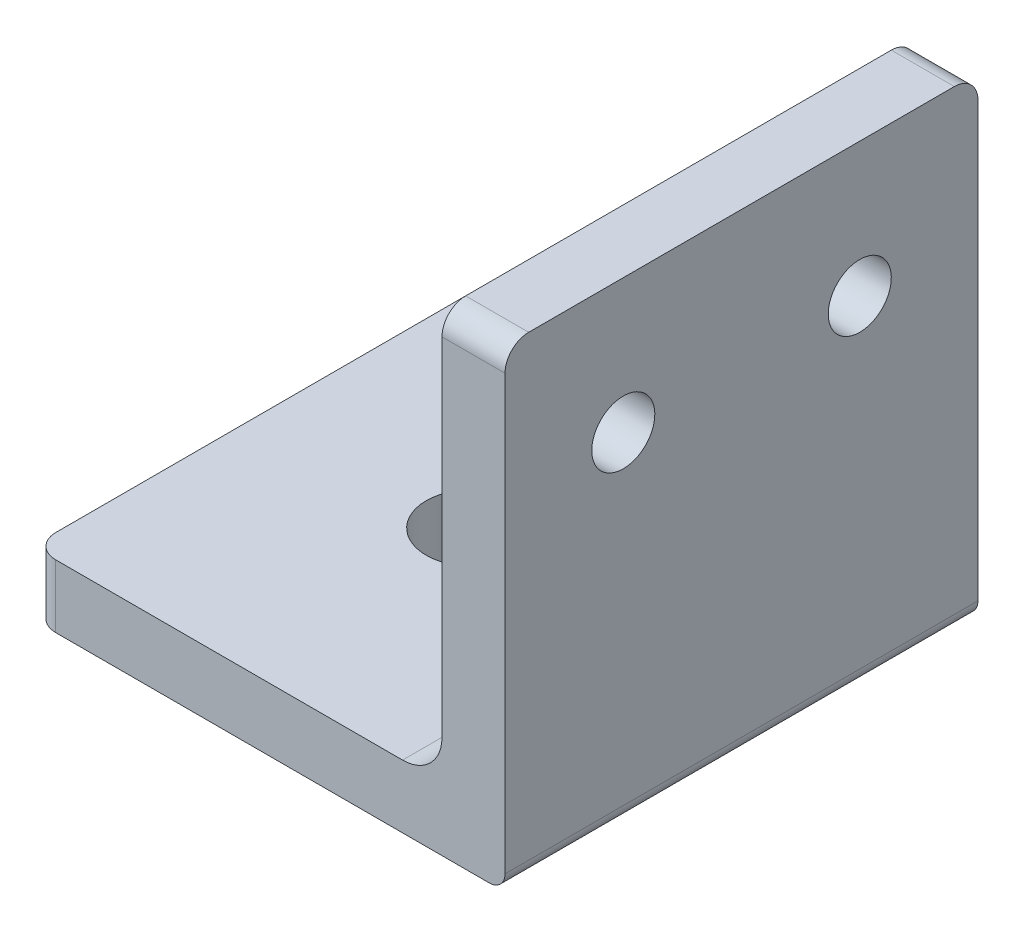
SolidWorks part; units mm, degrees
ref_plane "Front Plane" through (0, 0, 0) normal (0, 0, 1) x (1, 0, 0)
ref_plane "Top Plane" through (0, 0, 0) normal (0, 1, 0) x (1, 0, 0)
ref_plane "Right Plane" through (0, 0, 0) normal (1, 0, 0) x (0, 0, -1)
sketch "Sketch1" plane through (0, 0, 0) normal (0, 0, 1) x (1, 0, 0)
  line L0 (0, 0) -> (-52, 0)
  line L1 (-52, 0) -> (-52, -8)
  line L2 (-52, -8) -> (8, -8)
  line L3 (8, -8) -> (8, 52)
  line L4 (8, 52) -> (0, 52)
  line L5 (0, 52) -> (0, 0)
  point P3 (0, 0)
  dimension "D1" = 60
  dimension "D2" = 8
  dimension "D3" = 60
  dimension "D4" = 8
extrude "Boss-Extrude2" add sketch "Sketch1" along normal blind 60 contours L0 L1 L2 L3 L4 L5
sketch "Sketch3" plane through (0, 0, 0) normal (-1, 0, 0) x (0, 0, 1)
  line L0 (0, 52) -> (0, 0) construction
  line L1 (60, 0) -> (0, 0) construction
  line L2 (30, 54.8117) -> (30, -11.2228) construction
  circle A0 centre (15, 35) radius 4
  circle A1 centre (45, 35) radius 4
  dimension "D1" = 8
  dimension "D2" = 15
  dimension "D3" = 35
  dimension "D4" = 30
extrude "Cut-Extrude1" cut sketch "Sketch3" against normal blind 60
sketch "Sketch4" plane through (0, 0, 0) normal (0, 1, 0) x (1, 0, 0)
  line L0 (0, -60) -> (-52, -60) construction
  line L1 (0, -60) -> (0, 0) construction
  circle A0 centre (-26, -30) radius 6
  dimension "D1" = 12
  dimension "D2" = 30
  dimension "D3" = 26
extrude "Cut-Extrude2" cut sketch "Sketch4" against normal blind 60
fillet "Fillet1" radius 3 4 edges at (-52, -4, 60) (-52, -4, 0) (4, 52, 0) (4, 52, 60)
fillet "Fillet2" radius 5 1 edges at (0, 0, 30)
fillet "Fillet3" radius 2 1 edges at (8, -8, 30)
